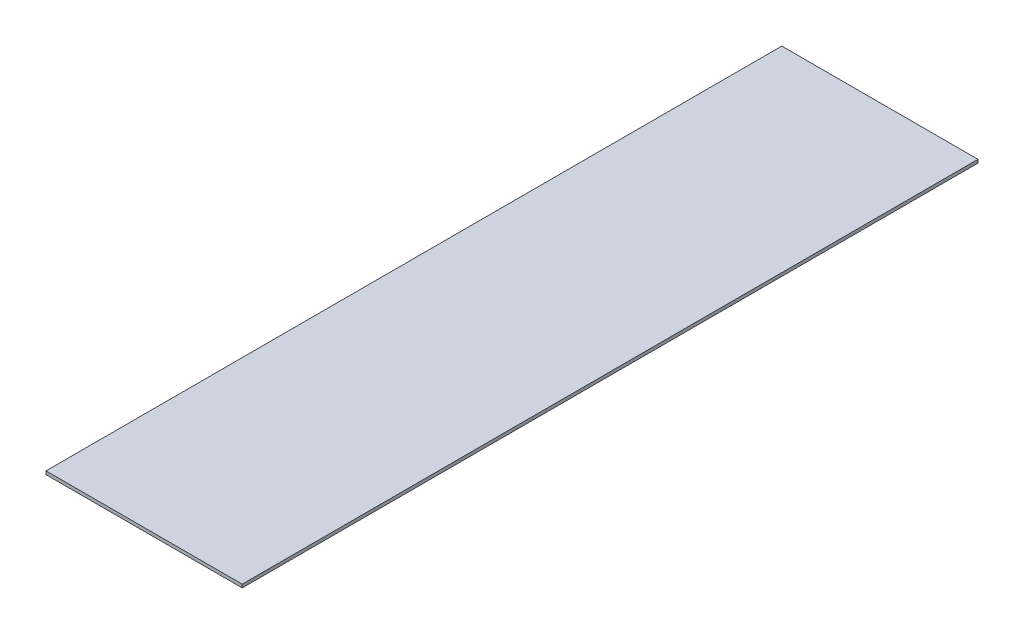
SolidWorks part; units mm, degrees
ref_plane "Front Plane" through (0, 0, 0) normal (0, 0, 1) x (1, 0, 0)
ref_plane "Top Plane" through (0, 0, 0) normal (0, 1, 0) x (1, 0, 0)
ref_plane "Right Plane" through (0, 0, 0) normal (1, 0, 0) x (0, 0, -1)
sketch "Sketch1" plane through (0, 0, 0) normal (0, 1, 0) x (1, 0, 0)
  line L1 (-20, 159.6591) -> (100, 159.6591)
  line L2 (-20, 159.6591) -> (-20, -290.3409)
  line L3 (-20, -290.3409) -> (100, -290.3409)
  line L4 (100, 159.6591) -> (100, -290.3409)
  dimension "D1" = 450
  dimension "D2" = 120
extrude "Boss-Extrude1" add sketch "Sketch1" along normal blind 2
